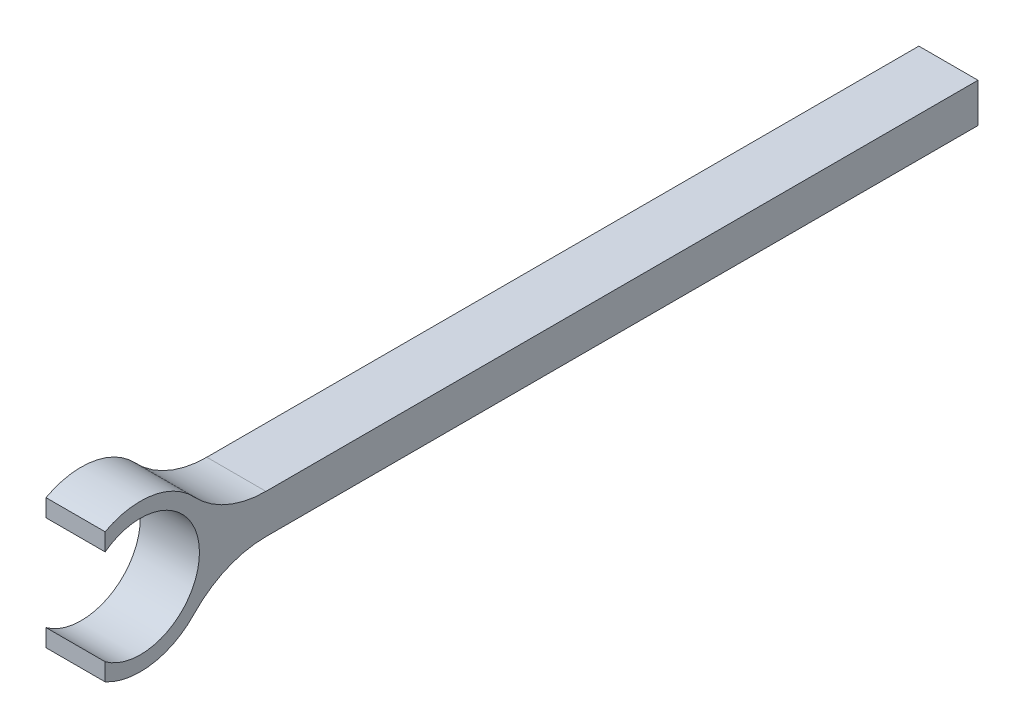
SolidWorks part; units mm, degrees
ref_plane "Front Plane" through (0, 0, 0) normal (0, 0, 1) x (1, 0, 0)
ref_plane "Top Plane" through (0, 0, 0) normal (0, 1, 0) x (1, 0, 0)
ref_plane "Right Plane" through (0, 0, 0) normal (1, 0, 0) x (0, 0, -1)
sketch "Sketch1" plane through (0, 0, 0) normal (1, 0, 0) x (0, 0, -1)
  line L0 (-3.5685, 23.6686) -> (-3.5685, -23.301)
  line L1 (0, 0) -> (109.6696, 0) construction
  line L2 (7.2312, -1.9901) -> (85, -1.9901)
  line L3 (85, -1.9901) -> (85, 1.9901)
  line L4 (7.2312, 1.9901) -> (85, 1.9901)
  line L9 (15, 32.3322) -> (15, -32.3322) construction
  circle A0 centre (0, 0) radius 7.5
  circle A1 centre (0, 0) radius 6
  point P8 (25.0172, 0)
  point P14 (85, 0)
  point P18 (15, 0)
  dimension "D1" = 12
  dimension "D2" = 1.5
  dimension "D4" = 70
extrude "Boss-Extrude1" add sketch "Sketch1" along normal blind 6
fillet "Fillet1" radius 10 2 edges at (3, 1.9901, -7.2312) (3, -1.9901, -7.2312)
